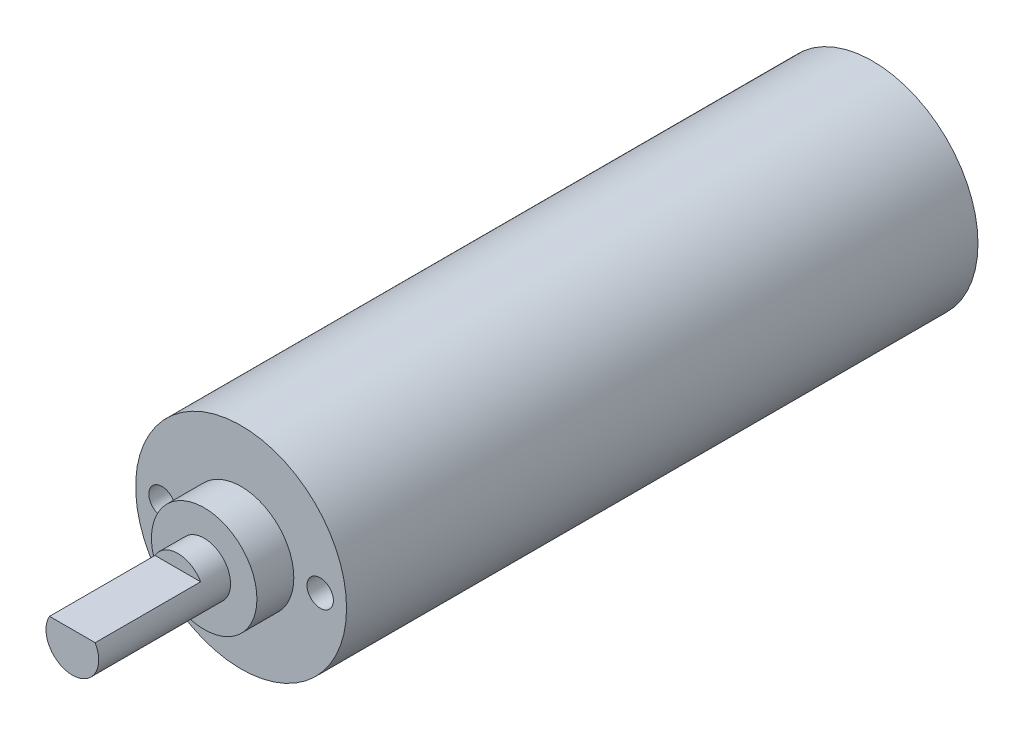
SolidWorks part; units mm, degrees
ref_plane "Plan de face" through (0, 0, 0) normal (0, 0, 1) x (1, 0, 0)
ref_plane "Plan de dessus" through (0, 0, 0) normal (0, 1, 0) x (1, 0, 0)
ref_plane "Plan de droite" through (0, 0, 0) normal (1, 0, 0) x (0, 0, -1)
sketch "Esquisse1" plane through (0, 0, 0) normal (0, 0, 1) x (1, 0, 0)
  circle A0 centre (0, 0) radius 8
  dimension "D1" = 16
extrude "Boss.-Extru.1" add sketch "Esquisse1" along normal blind 47.9
sketch "Esquisse2" plane through (0, 0, 47.9) normal (0, 0, 1) x (1, 0, 0)
  circle A0 centre (0, 0) radius 4
  dimension "D1" = 8
extrude "Boss.-Extru.2" add sketch "Esquisse2" along normal blind 2.8
sketch "Esquisse3" plane through (0, 0, 50.7) normal (0, 0, 1) x (1, 0, 0)
  circle A0 centre (0, 0) radius 2
  dimension "D1" = 4
extrude "Boss.-Extru.3" add sketch "Esquisse3" along normal blind 10
ref_plane "Plan1" through (0, 1, 0) normal (0, 1, 0) x (1, 0, 0)
sketch "Esquisse5" plane through (0, 1, 0) normal (0, 1, 0) x (1, 0, 0)
  line L0 (-2, -50.7) -> (2, -50.7) construction
  line L1 (-2, -50.7) -> (-2, -60.7) construction
  line L2 (2, -60.7) -> (2, -50.7) construction
  line L3 (-2, -60.7) -> (2, -60.7) construction
  line L4 (-2, -50.7) -> (2, -50.7) construction
  line L5 (-2, -52.7) -> (-2, -60.7)
  line L6 (2, -60.7) -> (2, -52.7)
  line L7 (-2, -60.7) -> (2, -60.7)
  line L8 (-2, -52.7) -> (2, -52.7)
  dimension "D1" = 2
extrude "Enlèv. mat.-Extru.1" cut sketch "Esquisse5" along normal blind 10
sketch "Esquisse6" plane through (0, 0, 0) normal (0, 0, -1) x (-1, 0, 0)
  circle A0 centre (0, 0) radius 4
  dimension "D1" = 8
extrude "Boss.-Extru.4" add sketch "Esquisse6" along normal blind 1.5
sketch "Esquisse7" plane through (0, 0, 47.9) normal (0, 0, 1) x (1, 0, 0)
  line L0 (0, 0) -> (11.8905, 0) construction
  circle A0 centre (6, 0) radius 1
  circle A1 centre (-6, 0) radius 1
  point P10 (0, 0)
  dimension "D2" = 2
  dimension "D1" = 6
  dimension "D3" = 2
extrude "Enlèv. mat.-Extru.2" cut sketch "Esquisse7" against normal blind 6
